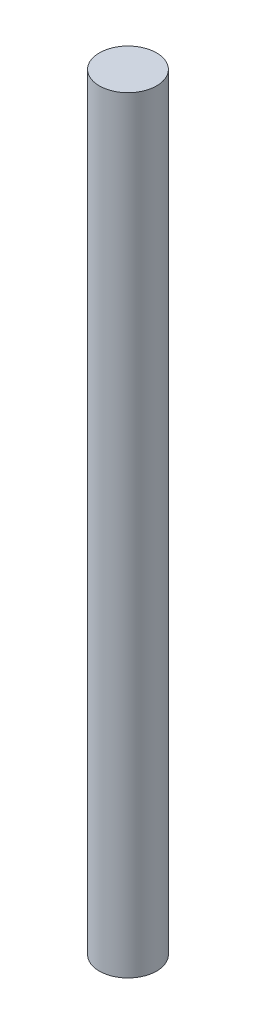
SolidWorks part; units mm, degrees
material "1060 Alloy"
ref_plane "Front Plane" through (0, 0, 0) normal (0, 0, 1) x (1, 0, 0)
ref_plane "Top Plane" through (0, 0, 0) normal (0, 1, 0) x (1, 0, 0)
ref_plane "Right Plane" through (0, 0, 0) normal (1, 0, 0) x (0, 0, -1)
sketch "Sketch1" plane through (0, 0, 0) normal (0, 1, 0) x (1, 0, 0)
  circle A0 centre (0, 0) radius 3.175
  dimension "D1" = 6.35
extrude "Boss-Extrude1" add sketch "Sketch1" along normal blind 85.09
